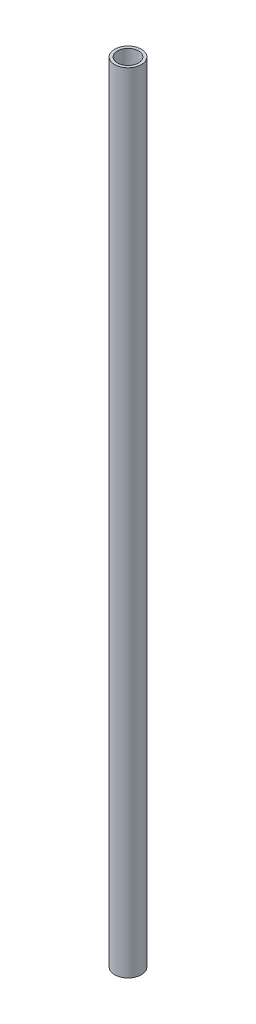
SolidWorks part; units mm, degrees
ref_plane "Front Plane" through (0, 0, 0) normal (0, 0, 1) x (1, 0, 0)
ref_plane "Top Plane" through (0, 0, 0) normal (0, 1, 0) x (1, 0, 0)
ref_plane "Right Plane" through (0, 0, 0) normal (1, 0, 0) x (0, 0, -1)
sketch "Sketch1" plane through (0, 0, 0) normal (0, 1, 0) x (1, 0, 0)
  circle A0 centre (0, 0) radius 12.7
  circle A1 centre (0, 0) radius 10
  dimension "D1" = 25.4
  dimension "D2" = 20
extrude "Boss-Extrude1" add sketch "Sketch1" along normal blind 750
